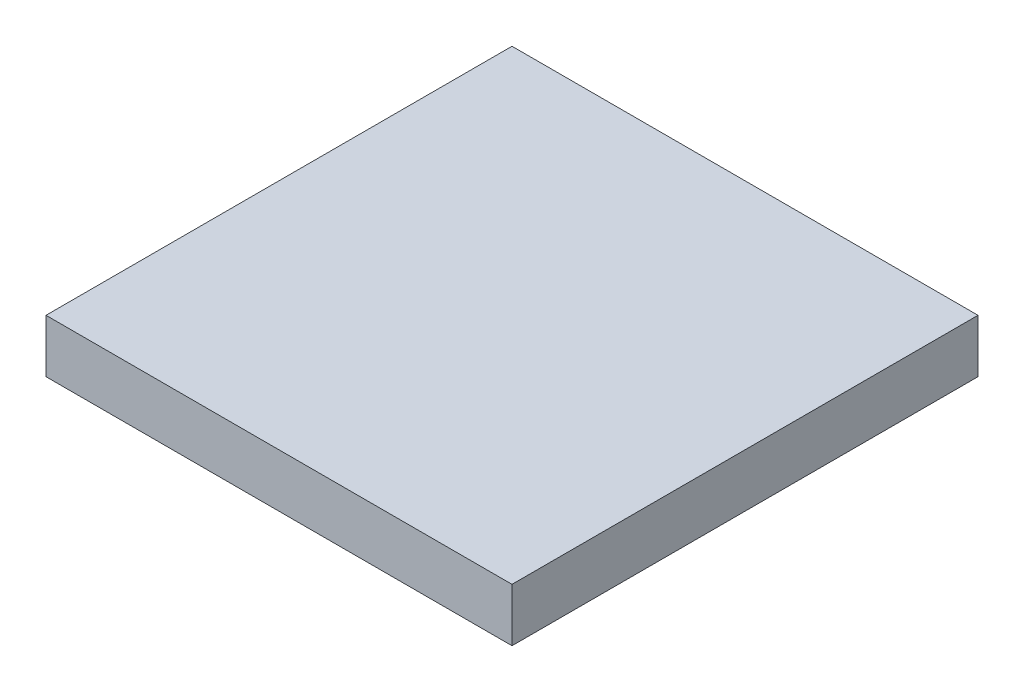
SolidWorks part; units mm, degrees
ref_plane "Front Plane" through (0, 0, 0) normal (0, 0, 1) x (1, 0, 0)
ref_plane "Top Plane" through (0, 0, 0) normal (0, 1, 0) x (1, 0, 0)
ref_plane "Right Plane" through (0, 0, 0) normal (1, 0, 0) x (0, 0, -1)
sketch "Sketch1" plane through (0, 0, 0) normal (0, 1, 0) x (1, 0, 0)
  line L1 (0, 0) -> (44.5, 0)
  line L2 (0, 0) -> (0, 44.5)
  line L3 (0, 44.5) -> (44.5, 44.5)
  line L4 (44.5, 0) -> (44.5, 44.5)
  dimension "D1" = 44.5
extrude "Boss-Extrude1" add sketch "Sketch1" along normal blind 5.08
